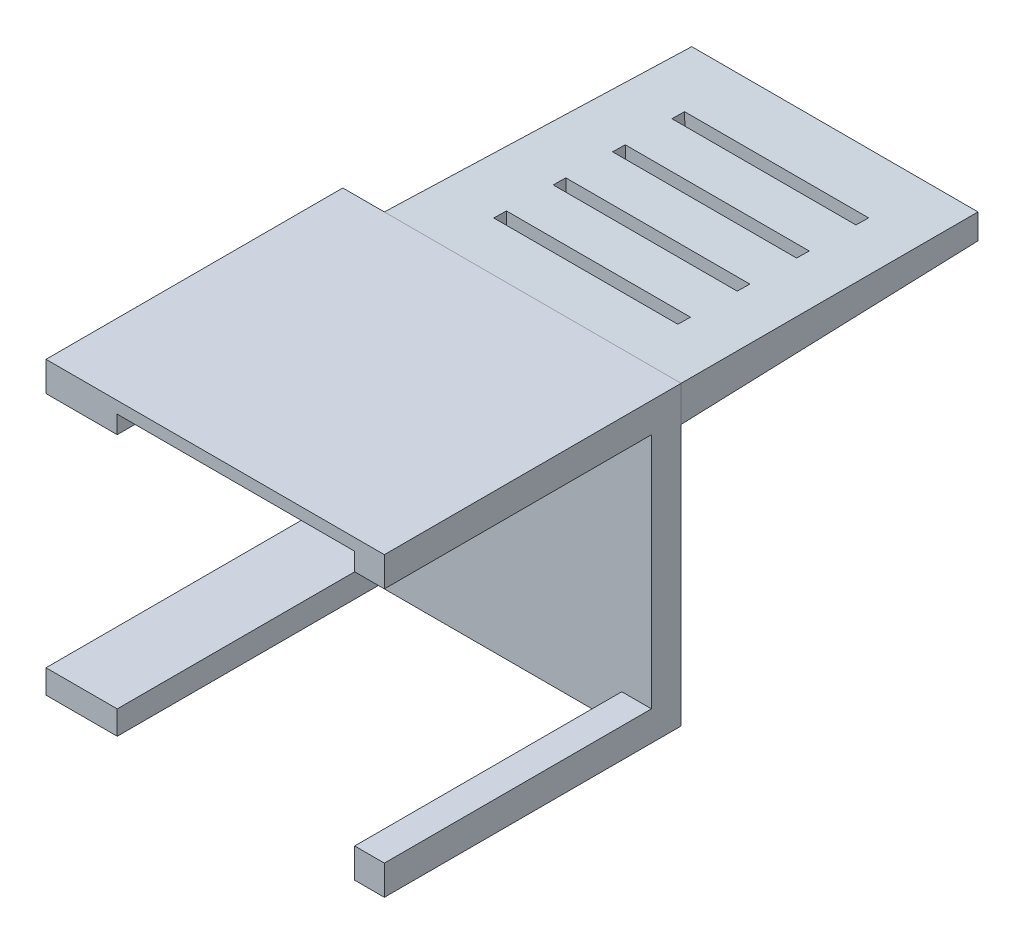
SolidWorks part; units mm, degrees
ref_plane "Front Plane" through (0, 0, 0) normal (0, 0, 1) x (1, 0, 0)
ref_plane "Top Plane" through (0, 0, 0) normal (0, 1, 0) x (1, 0, 0)
ref_plane "Right Plane" through (0, 0, 0) normal (1, 0, 0) x (0, 0, -1)
sketch "Sketch1" plane through (0, 0, 0) normal (0, 0, 1) x (1, 0, 0)
  line L1 (-256.7568, 132.6014) -> (243.2432, 132.6014)
  line L2 (-256.7568, 132.6014) -> (-256.7568, -367.3986)
  line L3 (-256.7568, -367.3986) -> (243.2432, -367.3986)
  line L4 (243.2432, 132.6014) -> (243.2432, -367.3986)
  dimension "D1" = 500
  dimension "D2" = 500
extrude "Boss-Extrude1" add sketch "Sketch1" along normal blind 50
sketch "Sketch2" plane through (0, 0, 50) normal (0, 0, 1) x (1, 0, 0)
  line L0 (-6.7568, 154.1935) -> (-6.7568, -357.6206) construction
  line L1 (-366.5446, -117.3986) -> (232.5473, -117.3986) construction
  line L2 (243.2432, -367.3986) -> (243.2432, 132.6014) construction
  line L3 (-256.7568, -367.3986) -> (243.2432, -367.3986) construction
  line L4 (-256.7568, 132.6014) -> (-256.7568, -367.3986) construction
  line L5 (-256.7568, 132.6014) -> (-206.7568, 132.6014)
  line L6 (-256.7568, 132.6014) -> (-256.7568, 82.6014)
  line L7 (-256.7568, 82.6014) -> (-206.7568, 82.6014)
  line L8 (-206.7568, 132.6014) -> (-206.7568, 82.6014)
  line L9 (243.2432, 132.6014) -> (-256.7568, 132.6014) construction
  line L10 (243.2432, 82.6014) -> (193.2432, 82.6014)
  line L11 (193.2432, 132.6014) -> (193.2432, 82.6014)
  line L12 (243.2432, 132.6014) -> (193.2432, 132.6014)
  line L13 (243.2432, 132.6014) -> (243.2432, 82.6014)
  line L14 (243.2432, -367.3986) -> (243.2432, -317.3986)
  line L15 (243.2432, -367.3986) -> (193.2432, -367.3986)
  line L16 (193.2432, -367.3986) -> (193.2432, -317.3986)
  line L17 (243.2432, -317.3986) -> (193.2432, -317.3986)
  line L18 (-256.7568, -317.3986) -> (-206.7568, -317.3986)
  line L19 (-206.7568, -367.3986) -> (-206.7568, -317.3986)
  line L20 (-256.7568, -367.3986) -> (-206.7568, -367.3986)
  line L21 (-256.7568, -367.3986) -> (-256.7568, -317.3986)
  dimension "D1" = 250
  dimension "D2" = 250
  dimension "D3" = 0
  dimension "D4" = 0
  dimension "D5" = 50
  dimension "D6" = 50
extrude "Boss-Extrude2" add sketch "Sketch2" along normal blind 450
sketch "Sketch3" plane through (0, 0, 50) normal (0, 0, 1) x (1, 0, 0)
  line L0 (-206.7568, 82.6014) -> (-206.7568, 132.6014) construction
  line L1 (-206.7568, 132.6014) -> (193.2432, 132.6014)
  line L2 (-206.7568, 132.6014) -> (-206.7568, 112.6014)
  line L3 (-206.7568, 112.6014) -> (193.2432, 112.6014)
  line L4 (193.2432, 132.6014) -> (193.2432, 112.6014)
  line L5 (193.2432, 132.6014) -> (-206.7568, 132.6014) construction
  line L6 (193.2432, 132.6014) -> (193.2432, 82.6014) construction
  dimension "D1" = 0
  dimension "D2" = 0
  dimension "D3" = 0
  dimension "D4" = 20
extrude "Boss-Extrude3" add sketch "Sketch3" along normal blind 450
sketch "Sketch4" plane through (0, 0, 0) normal (0, 0, -1) x (-1, 0, 0)
  line L1 (-243.2432, 132.6014) -> (256.7568, 132.6014)
  line L2 (-243.2432, 132.6014) -> (-243.2432, 72.6014)
  line L3 (-243.2432, 72.6014) -> (256.7568, 72.6014)
  line L4 (256.7568, 132.6014) -> (256.7568, 72.6014)
  dimension "D1" = 0
  dimension "D2" = 0
  dimension "D3" = 60
extrude "Boss-Extrude4" add sketch "Sketch4" along normal blind 509 draft 1
sketch "Sketch5" plane through (0, 72.5792, 1.2669) normal (0, -0.9998, -0.0175) x (1, 0, 0)
  line L1 (-157.2188, -387.1251) -> (142.7812, -387.1251)
  line L2 (-157.2188, -387.1251) -> (-157.2188, -408.4488)
  line L3 (-157.2188, -408.4488) -> (142.7812, -408.4488)
  line L4 (142.7812, -387.1251) -> (142.7812, -408.4488)
  line L7 (-147.2188, -387.1251) -> (-147.2188, -408.4488)
  line L8 (-147.2188, -387.1251) -> (152.7812, -387.1251)
  line L9 (152.7812, -387.1251) -> (152.7812, -408.4488)
  line L10 (-147.2188, -408.4488) -> (152.7812, -408.4488)
  line L11 (-147.2188, -287.1251) -> (-147.2188, -308.4488)
  line L12 (-147.2188, -287.1251) -> (152.7812, -287.1251)
  line L13 (152.7812, -287.1251) -> (152.7812, -308.4488)
  line L14 (-147.2188, -308.4488) -> (152.7812, -308.4488)
  line L15 (-147.2188, -187.1251) -> (-147.2188, -208.4488)
  line L16 (-147.2188, -187.1251) -> (152.7812, -187.1251)
  line L17 (152.7812, -187.1251) -> (152.7812, -208.4488)
  line L18 (-147.2188, -208.4488) -> (152.7812, -208.4488)
  line L19 (-147.2188, -87.1251) -> (-147.2188, -108.4488)
  line L20 (-147.2188, -87.1251) -> (152.7812, -87.1251)
  line L21 (152.7812, -87.1251) -> (152.7812, -108.4488)
  line L22 (-147.2188, -108.4488) -> (152.7812, -108.4488)
  line L23 (-157.2188, -287.1251) -> (-157.2188, -308.4488)
  line L24 (-157.2188, -287.1251) -> (142.7812, -287.1251)
  line L25 (142.7812, -287.1251) -> (142.7812, -308.4488)
  line L26 (-157.2188, -308.4488) -> (142.7812, -308.4488)
  line L27 (-157.2188, -187.1251) -> (-157.2188, -208.4488)
  line L28 (-157.2188, -187.1251) -> (142.7812, -187.1251)
  line L29 (142.7812, -187.1251) -> (142.7812, -208.4488)
  line L30 (-157.2188, -208.4488) -> (142.7812, -208.4488)
  line L31 (-157.2188, -87.1251) -> (-157.2188, -108.4488)
  line L32 (-157.2188, -87.1251) -> (142.7812, -87.1251)
  line L33 (142.7812, -87.1251) -> (142.7812, -108.4488)
  line L34 (-157.2188, -108.4488) -> (142.7812, -108.4488)
  dimension "D1" = 2
  dimension "D2" = 4
extrude "Cut-Extrude1" cut sketch "Sketch5" against normal blind 509 contours L1 L7 L3 L4 | L7 L1 L2 L3 | L4 L10 L9 L8 | L25 L12 L11 L14 | L12 L25 L14 L13 | L27 L30 L15 L28 | L29 L16 L15 L18 | L16 L29 L18 L17 | L31 L34 L19 L32 | L33 L20 L19 L22 | L20 L33 L22 L21
sketch "Sketch6" plane through (-256.7568, 0, 0) normal (-1, 0, 0) x (0, 0, 1)
  line L0 (500, 132.6014) -> (0, 132.6014) construction
  line L1 (0, 132.6014) -> (500, 132.6014)
  line L2 (0, 132.6014) -> (0, 82.6014)
  line L3 (0, 82.6014) -> (500, 82.6014)
  line L4 (500, 132.6014) -> (500, 82.6014)
  line L5 (0, 82.6014) -> (50, 82.6014)
  line L6 (0, 82.6014) -> (0, -367.3986)
  line L7 (0, -367.3986) -> (50, -367.3986)
  line L8 (50, 82.6014) -> (50, -367.3986)
  line L9 (50, -317.3986) -> (500, -317.3986)
  line L10 (50, -317.3986) -> (50, -367.3986)
  line L11 (50, -367.3986) -> (500, -367.3986)
  line L12 (500, -317.3986) -> (500, -367.3986)
  line L13 (0, 132.6014) -> (0, 72.6014) construction
  line L14 (500, 82.6014) -> (50, 82.6014) construction
  line L15 (500, 132.6014) -> (500, 82.6014) construction
  line L16 (50, 82.6014) -> (50, -317.3986) construction
  line L17 (0, 72.6014) -> (0, -367.3986) construction
  line L18 (500, -367.3986) -> (0, -367.3986) construction
  line L19 (500, -317.3986) -> (50, -317.3986) construction
  line L20 (500, -317.3986) -> (500, -367.3986) construction
  line M13 (0, 132.6014) -> (0, 72.6014)
  line M15 (0, -367.3986) -> (500, -367.3986)
  line M16 (500, -367.3986) -> (500, -317.3986)
  line M17 (500, -317.3986) -> (50, -317.3986)
  line M19 (50, 82.6014) -> (500, 82.6014)
  line M20 (500, 82.6014) -> (500, 132.6014)
  line M21 (500, 132.6014) -> (0, 132.6014)
  dimension "D1" = 0
  dimension "D2" = 0
  dimension "D3" = 0
  dimension "D4" = 0
  dimension "D5" = 0
  dimension "D6" = 0
  dimension "D7" = 0
  dimension "D8" = 0
  dimension "D9" = 0
  dimension "D10" = 0
  dimension "D11" = 0
  dimension "D12" = 0
extrude "Boss-Extrude5" add sketch "Sketch6" along normal blind 70 contours L8 M17 M15 M16 | L3 M13 M19 M20 M21
sketch "Sketch7" plane through (0, -367.3986, 0) normal (0, -1, 0) x (1, 0, 0)
  line L0 (-326.7568, 0) -> (-326.7568, 500) construction
  line L1 (-326.7568, 500) -> (-206.7568, 500)
  line L2 (-326.7568, 500) -> (-326.7568, 50)
  line L3 (-326.7568, 50) -> (-206.7568, 50)
  line L4 (-206.7568, 500) -> (-206.7568, 50)
  line L5 (-326.7568, 500) -> (-206.7568, 500) construction
  line L6 (-206.7568, 50) -> (193.2432, 50) construction
  line L7 (-206.7568, 500) -> (-206.7568, 50) construction
  dimension "D1" = 0
  dimension "D2" = 0
  dimension "D3" = 0
  dimension "D4" = 0
extrude "Cut-Extrude2" cut sketch "Sketch7" against normal blind 10
